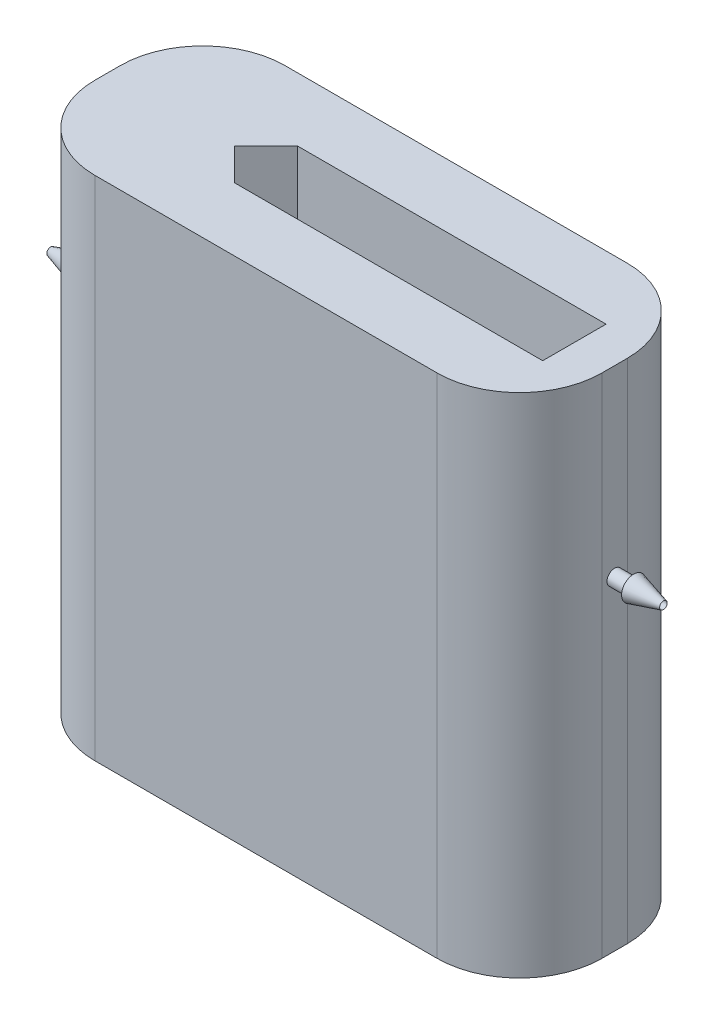
SolidWorks part; units mm, degrees
ref_plane "Front Plane" through (0, 0, 0) normal (0, 0, 1) x (1, 0, 0)
ref_plane "Top Plane" through (0, 0, 0) normal (0, 1, 0) x (1, 0, 0)
ref_plane "Right Plane" through (0, 0, 0) normal (1, 0, 0) x (0, 0, -1)
sketch "Sketch1" plane through (0, 0, 0) normal (0, 1, 0) x (1, 0, 0)
  line L1 (-40, -15) -> (40, -15)
  line L2 (-40, -15) -> (-40, 15)
  line L3 (-40, 15) -> (40, 15)
  line L4 (40, -15) -> (40, 15)
  line L5 (-40, -15) -> (40, 15) construction
  line L6 (-40, 15) -> (40, -15) construction
  point P0 (0, 0)
  dimension "D1" = 30
  dimension "D2" = 80
extrude "Boss-Extrude1" add sketch "Sketch1" along normal blind 80
sketch "Sketch2" plane through (0, 80, 0) normal (0, 1, 0) x (1, 0, 0)
  line L0 (-15, 5) -> (15, 5)
  line L3 (15, -5) -> (-15, -5)
  line L4 (-15, -5) -> (-20, 0)
  line L5 (-20, 0) -> (-15, 5)
  line L6 (15, 5) -> (33.657, 5)
  line L7 (33.657, 5) -> (33.657, -5)
  line L8 (33.657, -5) -> (15, -5)
  dimension "D1" = 15
  dimension "D2" = 15
  dimension "D3" = 15
  dimension "D4" = 15
  dimension "D5" = 5
  dimension "D6" = 5
extrude "Cut-Extrude1" cut sketch "Sketch2" against normal blind 75
sketch "Sketch3" plane through (-40, 0, 0) normal (-1, 0, 0) x (0, 0, 1)
  circle A0 centre (0, 51.112) radius 0.8
  dimension "D1" = 1.6
extrude "Cut-Extrude2" cut sketch "Sketch3" against normal through all and the other way through all
sketch "Sketch4" plane through (-40, 0, 0) normal (-1, 0, 0) x (0, 0, 1)
  circle A0 centre (0, 51.112) radius 1.5
  circle A1 centre (0, 51.112) radius 1.2
  dimension "D1" = 2.4
  dimension "D2" = 3
extrude "Boss-Extrude2" add sketch "Sketch4" along normal blind 3
sketch "Sketch6" plane through (0, 0, 0) normal (0, 0, 1) x (1, 0, 0)
  line L0 (-43, 51.112) -> (-49.3252, 51.112)
  line L1 (-43, 52.612) -> (-43, 49.612) construction
  line L2 (-43, 51.112) -> (-43, 53.512)
  line L3 (-43, 53.512) -> (-49.3252, 51.612)
  line L4 (-49.3252, 51.612) -> (-49.3252, 51.112)
  dimension "D1" = 2.4
  dimension "D2" = 0.5
revolve "Revolve1" add sketch "Sketch6" angle 360 about L0
sketch "Sketch7" plane through (-49.3252, 0, 0) normal (-1, 0, 0) x (0, 0, 1)
  circle A0 centre (0, 51.112) radius 0.6
  dimension "D1" = 1.2
extrude "Cut-Extrude3" cut sketch "Sketch7" against normal blind 2
sketch "Sketch8" plane through (-47.3252, 0, 0) normal (-1, 0, 0) x (0, 0, 1)
  circle A0 centre (0, 51.112) radius 0.8
  dimension "D1" = 1.6
extrude "Cut-Extrude4" cut sketch "Sketch8" against normal blind 53
fillet "Fillet1" radius 13 4 edges at (40, 40, -15) (-40, 40, -15) (40, 40, 15) (-40, 40, 15)
sketch "Sketch9" plane through (40, 0, 0) normal (1, 0, 0) x (0, 0, -1)
  circle A0 centre (0, 51.112) radius 0.8
  circle A1 centre (0, 51.112) radius 1.2
  dimension "D1" = 2.4
extrude "Boss-Extrude3" add sketch "Sketch9" along normal blind 3
sketch "Sketch11" plane through (0, 0, 0) normal (0, 0, 1) x (1, 0, 0)
  line L0 (43, 51.112) -> (43, 53.0133)
  line L1 (43, 49.912) -> (43, 52.312) construction
  line L2 (43, 51.112) -> (47.7051, 51.112)
  line L3 (47.7051, 51.112) -> (47.7051, 51.712)
  line L4 (47.7051, 51.712) -> (43, 53.0133)
  dimension "D1" = 0.6
  dimension "D2" = 1.9014
  dimension "D3" = 4.7051
revolve "Revolve2" add sketch "Sketch11" angle 360 about L2
sketch "Sketch12" plane through (47.7051, 0, 0) normal (1, 0, 0) x (0, 0, -1)
  circle A0 centre (0, 51.112) radius 0.6
extrude "Cut-Extrude5" cut sketch "Sketch12" against normal blind 2
sketch "Sketch14" plane through (45.7051, 0, 0) normal (1, 0, 0) x (0, 0, -1)
  circle A0 centre (0, 51.112) radius 0.8
extrude "Cut-Extrude6" cut sketch "Sketch14" against normal blind 35
